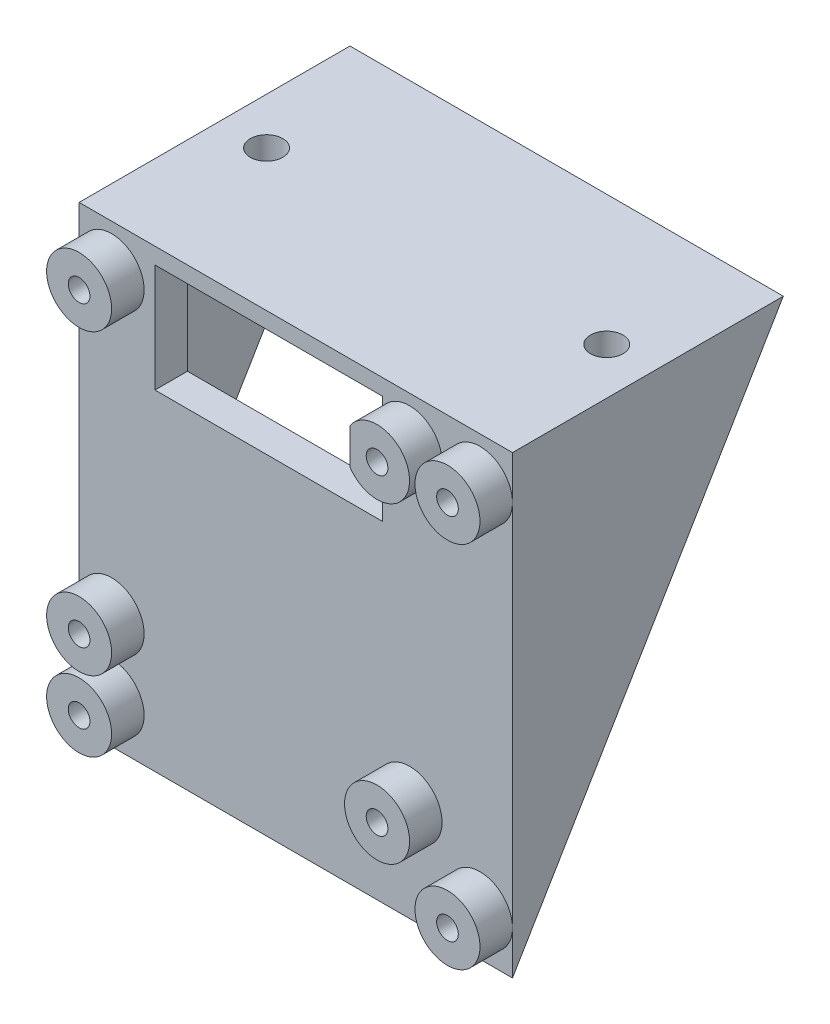
SolidWorks part; units mm, degrees
other "标注1"
sketch "草图6" plane through (0, 0.634, 23.0981) normal (-0.1957, 0.3965, 0.8969) x (0.9455, 0.319, 0.0653)
material "PLA - Blue"
ref_plane "前视基准面" through (0, 0, 0) normal (0, 0, 1) x (1, 0, 0)
ref_plane "上视基准面" through (0, 0, 0) normal (0, 1, 0) x (1, 0, 0)
ref_plane "右视基准面" through (0, 0, 0) normal (1, 0, 0) x (0, 0, -1)
other "Configuration Table"
sketch "草图1" plane through (0, 0, 0) normal (1, 0, 0) x (0, 0, -1)
  line L0 (0, 0) -> (0, -42)
  line L1 (0, -42) -> (25, 0)
  line L2 (25, 0) -> (0, 0)
  dimension "D1" = 90
  dimension "D2" = 42
  dimension "D3" = 25
extrude "凸台-拉伸1" add sketch "草图1" along normal blind 40
ref_plane "基准面1" through (38, 0, 0) normal (1, 0, 0) x (0, 0, -1)
sketch "草图2" plane through (38, 0, 0) normal (1, 0, 0) x (0, 0, -1)
  line L0 (23.8314, -3) -> (3, -3)
  line L1 (3, -3) -> (3, -33.0681)
  line L2 (3, -33.0681) -> (23.8314, -33.0681)
  line L3 (23.8314, -33.0681) -> (23.8314, -3)
  line L4 (25, 0) -> (0, 0) construction
  line L5 (0, 0) -> (0, -42) construction
  dimension "D1" = 3
  dimension "D2" = 3
extrude "切除-拉伸1" cut sketch "草图2" against normal blind 36
sketch "草图3" plane through (0, 0, 0) normal (0, 1, 0) x (1, 0, 0)
  line L0 (20, 25) -> (20, 0) construction
  line L1 (40, 25) -> (0, 25) construction
  line L2 (40, 0) -> (0, 0) construction
  circle A0 centre (4.3, 13) radius 1.5
  circle A1 centre (35.7, 13) radius 1.5
  dimension "D3" = 3
  dimension "D4" = 3
  dimension "D1" = 31.4
  dimension "D2" = 15.7
  dimension "D5" = 12
  dimension "D6" = 12
extrude "切除-拉伸2" cut sketch "草图3" against normal blind 32
sketch "草图4" plane through (0, 0, 0) normal (0, 0, 1) x (1, 0, 0)
  line L0 (0, -21) -> (40, -21) construction
  line L1 (0, 0) -> (0, -42) construction
  line L2 (40, 0) -> (40, -42) construction
  line L3 (20, 0) -> (20, -42) construction
  line L4 (40, 0) -> (0, 0) construction
  line L5 (40, -42) -> (0, -42) construction
  circle A0 centre (3, -4) radius 3
  circle A1 centre (37, -4) radius 3
  circle A2 centre (37, -38) radius 3
  circle A3 centre (3, -38) radius 3
  circle A4 centre (3, -4) radius 1
  circle A5 centre (37, -4) radius 1
  circle A6 centre (37, -38) radius 1
  circle A7 centre (3, -38) radius 1
  circle A8 centre (30.5, -4) radius 1
  circle A9 centre (30.5, -4) radius 3
  circle A10 centre (30.5, -32.8209) radius 3
  circle A11 centre (30.5, -32.8209) radius 1
  circle A12 centre (3, -31.5) radius 1
  circle A13 centre (3, -31.5) radius 3
  dimension "D9" = 6
  dimension "D10" = 6
  dimension "D11" = 6
  dimension "D12" = 6
  dimension "D13" = 2
  dimension "D14" = 2
  dimension "D15" = 2
  dimension "D16" = 2
  dimension "D18" = 2
  dimension "D19" = 6
  dimension "D20" = 6
  dimension "D21" = 2
  dimension "D22" = 6
  dimension "D23" = 2
  dimension "D1" = 17
  dimension "D2" = 17
  dimension "D3" = 17
  dimension "D4" = 17
  dimension "D5" = 17
  dimension "D6" = 17
  dimension "D7" = 17
  dimension "D8" = 17
  dimension "D17" = 27.5
  dimension "D24" = 27.5
extrude "凸台-拉伸2" add sketch "草图4" along normal blind 3 and the other way blind 1
sketch "草图5" plane through (0, 0, 3) normal (0, 0, 1) x (1, 0, 0)
  line L0 (20, 0) -> (20, -42) construction
  line L1 (40, 0) -> (0, 0) construction
  line L2 (40, -42) -> (0, -42) construction
  line L3 (20, -1.5) -> (7, -1.5)
  line L4 (20, -11.5) -> (28, -11.5)
  line L6 (20, -1.5) -> (28, -1.5)
  line L7 (28, -11.5) -> (28, -1.5)
  line L8 (7, -1.5) -> (7, -11.5)
  line L9 (7, -11.5) -> (20, -11.5)
  circle A0 centre (3, -4) radius 1
  circle A1 centre (37, -4) radius 1
  circle A2 centre (37, -38) radius 0.9283
  circle A3 centre (3, -38) radius 1
  point P18 (20, -6.5)
  dimension "D1" = 10
  dimension "D2" = 13
  dimension "D3" = 1.5
  dimension "D4" = 8
extrude "切除-拉伸3" cut sketch "草图5" against normal through all
